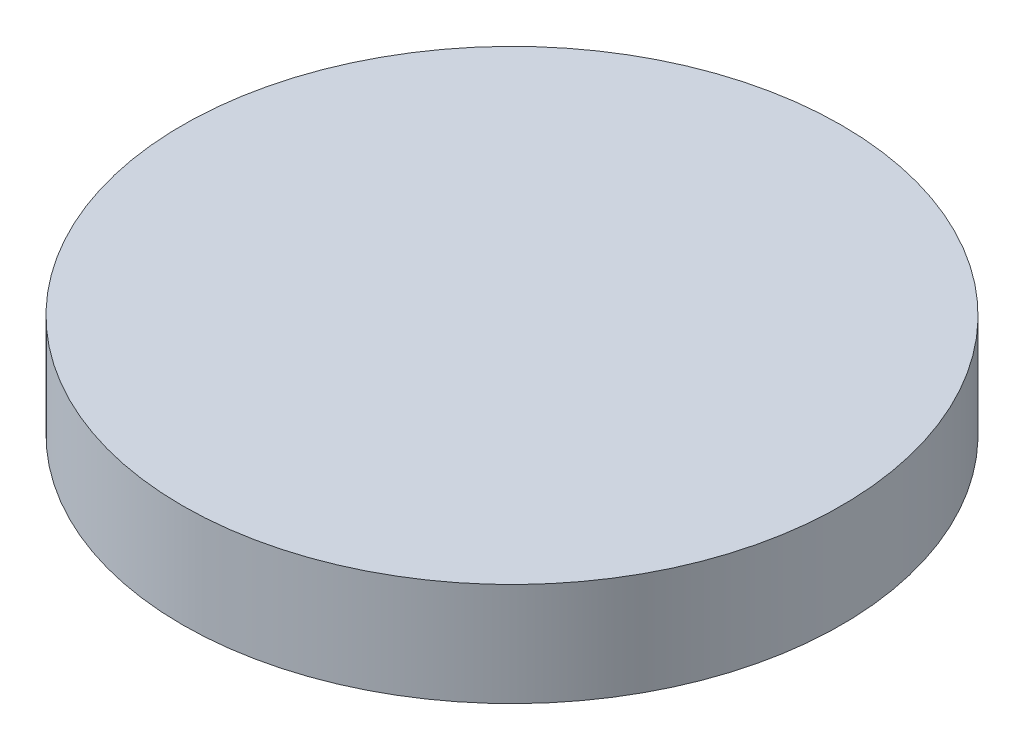
SolidWorks part; units mm, degrees
ref_plane "Front Plane" through (0, 0, 0) normal (0, 0, 1) x (1, 0, 0)
ref_plane "Top Plane" through (0, 0, 0) normal (0, 1, 0) x (1, 0, 0)
ref_plane "Right Plane" through (0, 0, 0) normal (1, 0, 0) x (0, 0, -1)
sketch "Sketch1" plane through (0, 0, 0) normal (0, 1, 0) x (1, 0, 0)
  circle A0 centre (0, 0) radius 5.75
  point P3 (0, 0)
  dimension "D1" = 11.5
extrude "Boss-Extrude1" add sketch "Sketch1" along normal blind 1.8
